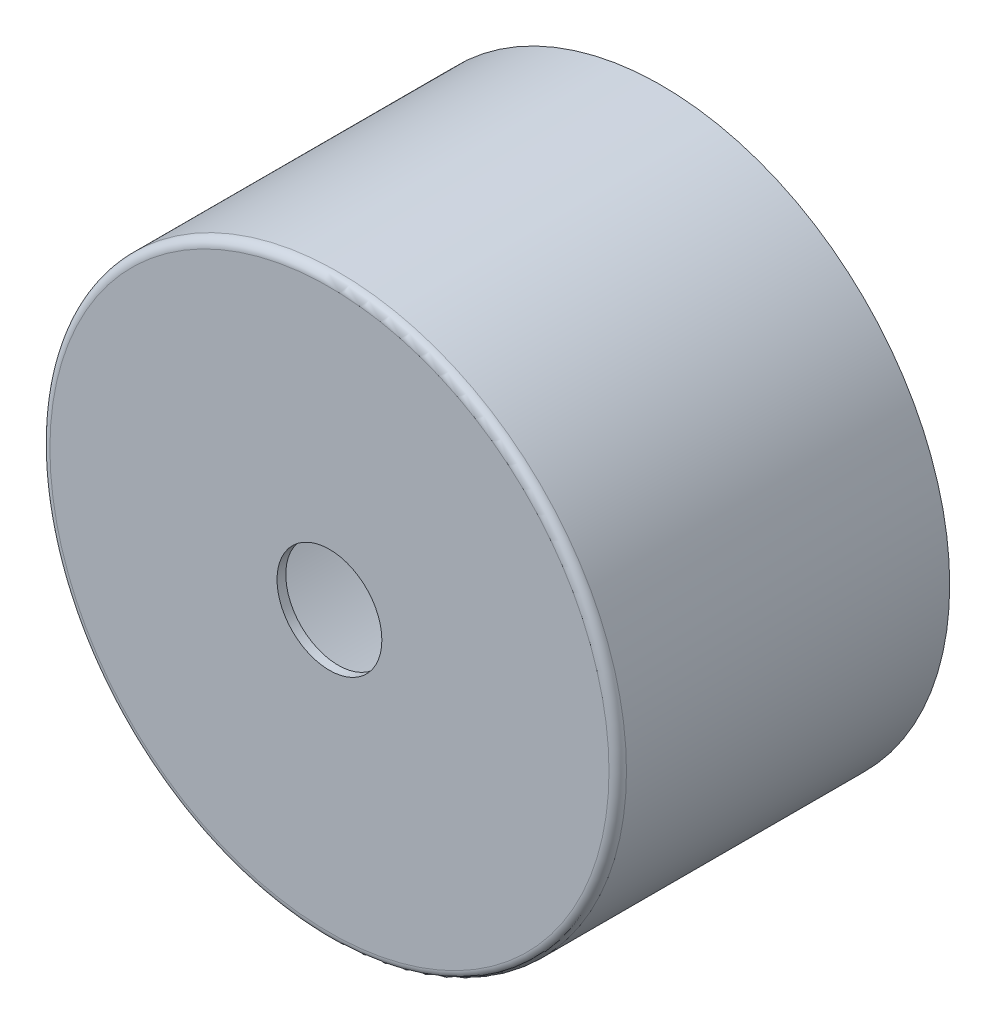
SolidWorks part; units mm, degrees
ref_plane "Front Plane" through (0, 0, 0) normal (0, 0, 1) x (1, 0, 0)
ref_plane "Top Plane" through (0, 0, 0) normal (0, 1, 0) x (1, 0, 0)
ref_plane "Right Plane" through (0, 0, 0) normal (1, 0, 0) x (0, 0, -1)
sketch "Sketch1" plane through (0, 0, 0) normal (0, 0, 1) x (1, 0, 0)
  circle A0 centre (0, 0) radius 16.5
  dimension "D1" = 33
extrude "Boss-Extrude1" add sketch "Sketch1" against normal blind 19
shell "Shell1" thickness 0.5
sketch "Sketch2" plane through (0, 0, 0) normal (0, 0, 1) x (1, 0, 0)
  circle A0 centre (0, 0) radius 3
  dimension "D1" = 6
extrude "Cut-Extrude1" cut sketch "Sketch2" against normal through all
fillet "Fillet1" radius 0.5 1 edges at (16.5, 0, 0)
